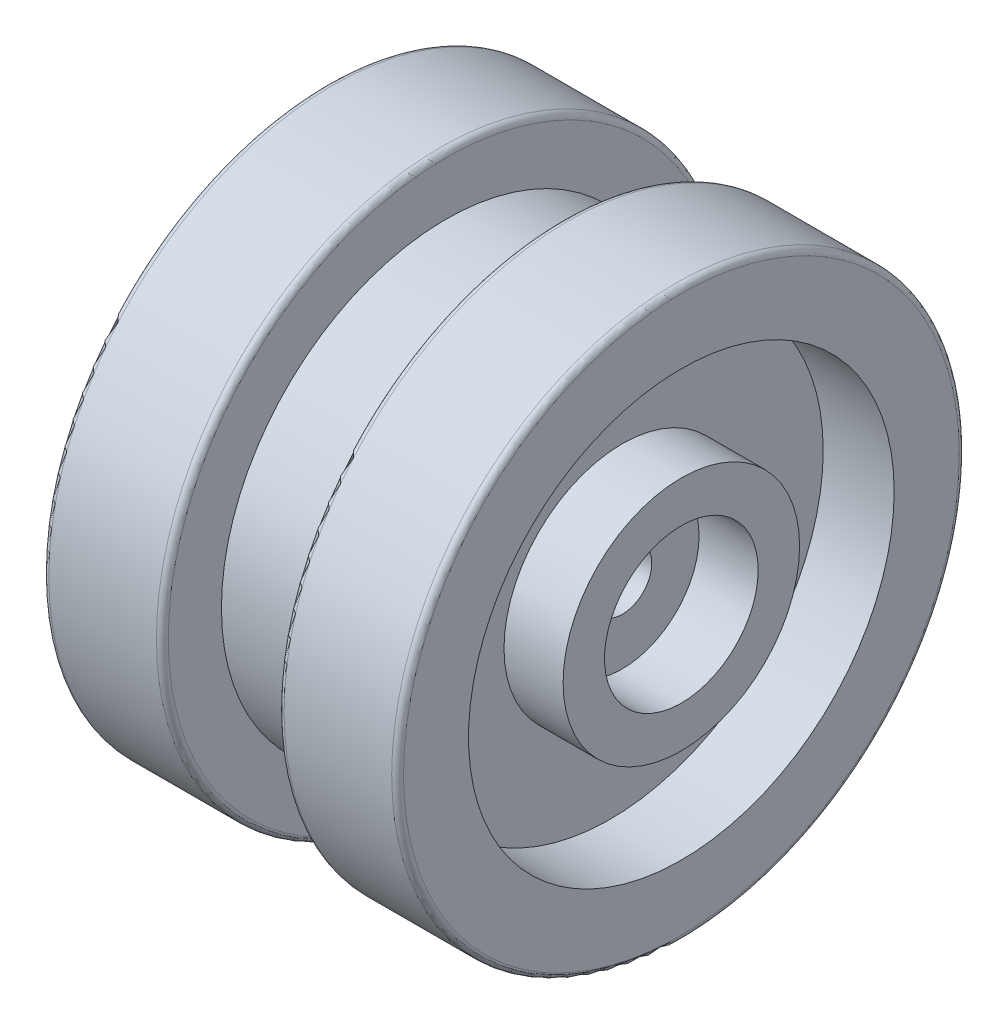
SolidWorks part; units mm, degrees
ref_plane "Front Plane" through (0, 0, 0) normal (0, 0, 1) x (1, 0, 0)
ref_plane "Top Plane" through (0, 0, 0) normal (0, 1, 0) x (1, 0, 0)
ref_plane "Right Plane" through (0, 0, 0) normal (1, 0, 0) x (0, 0, -1)
sketch "Sketch2" plane through (0, 0, 0) normal (0, 0, 1) x (1, 0, 0)
  line L0 (-2.5652, 0.5157) -> (7.2348, 0.5157)
  line L1 (-2.5652, 0.5157) -> (-2.5652, 5.5157)
  line L2 (7.2348, 0.5157) -> (7.2348, 5.5157)
  line L3 (7.2348, 5.5157) -> (17.3348, 5.5157)
  line L4 (-2.5652, 5.5157) -> (-12.6652, 5.5157)
  line L5 (-12.6652, 5.5157) -> (-12.6652, -18.4843)
  line L6 (-12.6652, -18.4843) -> (17.3348, -18.4843)
  line L7 (17.3348, -18.4843) -> (17.3348, 5.5157)
  line L8 (-12.6652, -18.4843) -> (27.3603, -18.4843) construction
revolve "Revolve1" add sketch "Sketch2" angle 360 about L8
sketch "Sketch3" plane through (17.3348, 0, 0) normal (1, 0, 0) x (0, 0, -1)
  circle A0 centre (0, -18.4843) radius 2
extrude "Cut-Extrude1" cut sketch "Sketch3" against normal through all
fillet "Fillet2" radius 0.5 4 edges at (-2.5652, -18.4843, 24) (7.2348, -18.4843, 24) (17.3348, -18.4843, 24) (-12.6652, -18.4843, 24)
sketch "Sketch4" plane through (17.3348, 0, 0) normal (1, 0, 0) x (0, 0, -1)
  circle A0 centre (0, -18.4843) radius 6
  circle A1 centre (0, -18.4843) radius 18
extrude "Cut-Extrude2" cut sketch "Sketch4" against normal blind 6
sketch "Sketch5" plane through (-12.6652, 0, 0) normal (-1, 0, 0) x (0, 0, 1)
  circle A0 centre (0, -18.4843) radius 6
  circle A1 centre (0, -18.4843) radius 18
extrude "Cut-Extrude3" cut sketch "Sketch5" against normal blind 6 contours A1
sketch "Sketch6" plane through (-6.6652, 0, 0) normal (-1, 0, 0) x (0, 0, 1)
  circle A0 centre (0, -18.4843) radius 10
extrude "Boss-Extrude1" add sketch "Sketch6" along normal through all
sketch "Sketch7" plane through (-12.6652, 0, 0) normal (-1, 0, 0) x (0, 0, 1)
  circle A0 centre (0, -18.4843) radius 2.5
sketch "Sketch8" plane through (17.3348, 0, 0) normal (1, 0, 0) x (0, 0, -1)
  circle A0 centre (0, -18.4843) radius 8
extrude "Boss-Extrude2" add sketch "Sketch8" against normal blind 10 contours A0
sketch "Sketch9" plane through (17.3348, 0, 0) normal (1, 0, 0) x (0, 0, -1)
  circle A0 centre (0, -18.4843) radius 6.5
sketch "Sketch10" plane through (-12.6652, 0, 0) normal (-1, 0, 0) x (0, 0, 1)
  circle A0 centre (0, -18.4843) radius 6.5
extrude "Cut-Extrude5" cut sketch "Sketch10" against normal blind 5 contours A0
sketch "Sketch11" plane through (17.3348, 0, 0) normal (1, 0, 0) x (0, 0, -1)
  circle A0 centre (0, -18.4843) radius 10
extrude "Boss-Extrude3" add sketch "Sketch11" against normal blind 5
sketch "Sketch12" plane through (17.3348, 0, 0) normal (1, 0, 0) x (0, 0, -1)
  circle A0 centre (0, -18.4843) radius 6.5
extrude "Cut-Extrude6" cut sketch "Sketch12" against normal blind 5
extrude "Cut-Extrude8" cut sketch "Sketch7" against normal through all contours A0
